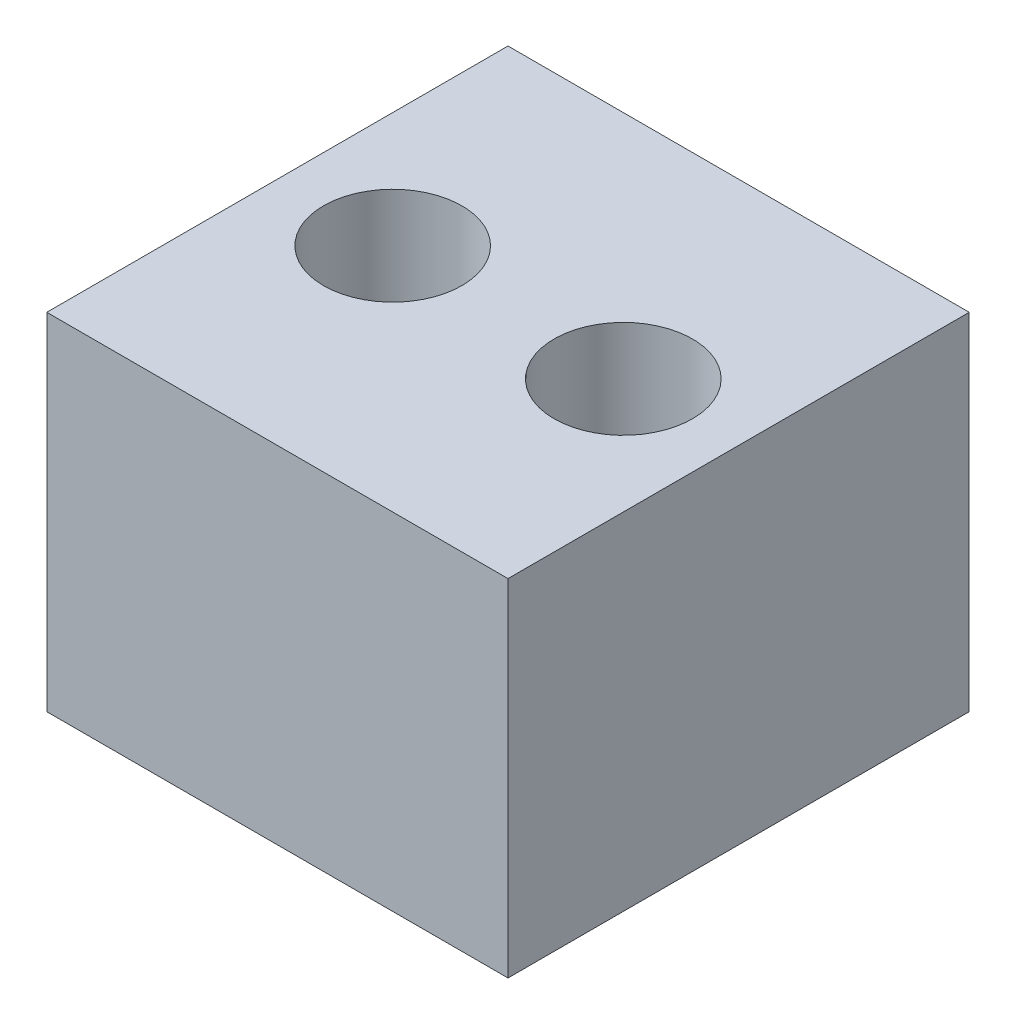
SolidWorks part; units mm, degrees
material "Copper"
ref_plane "Front Plane" through (0, 0, 0) normal (0, 0, 1) x (1, 0, 0)
ref_plane "Top Plane" through (0, 0, 0) normal (0, 1, 0) x (1, 0, 0)
ref_plane "Right Plane" through (0, 0, 0) normal (1, 0, 0) x (0, 0, -1)
sketch "Sketch1" plane through (0, 0, 0) normal (0, 1, 0) x (1, 0, 0)
  line L1 (-10, 10) -> (10, 10)
  line L2 (-10, 10) -> (-10, -10)
  line L3 (-10, -10) -> (10, -10)
  line L4 (10, 10) -> (10, -10)
  line L5 (-10, 10) -> (10, -10) construction
  line L6 (-10, -10) -> (10, 10) construction
  point P0 (0, 0)
  dimension "D1" = 20
  dimension "D2" = 20
extrude "Boss-Extrude1" add sketch "Sketch1" along normal blind 15
sketch "Sketch2" plane through (0, 15, 0) normal (0, 1, 0) x (1, 0, 0)
  line L0 (0, 0) -> (5, 0) construction
  line L1 (0, 0) -> (-5, 0) construction
  circle A0 centre (5, 0) radius 3
  circle A1 centre (-5, 0) radius 3
  dimension "D3" = 6
  dimension "D4" = 6
  dimension "D1" = 5
  dimension "D2" = 5
extrude "Cut-Extrude1" cut sketch "Sketch2" against normal blind 5
